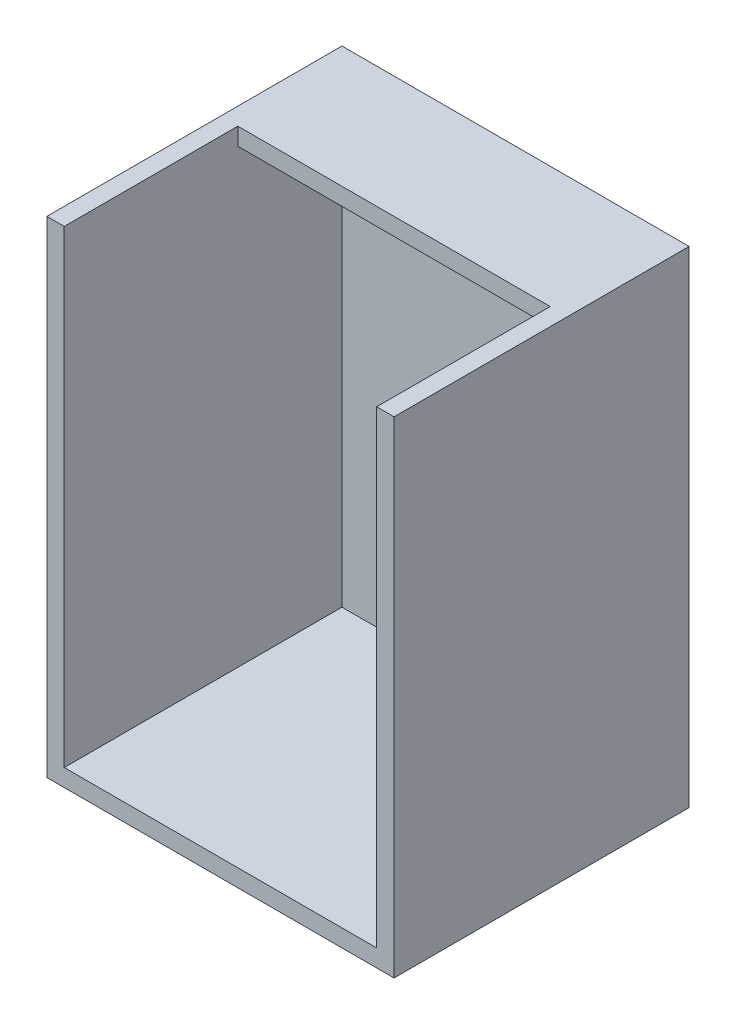
SolidWorks part; units mm, degrees
ref_plane "Front Plane" through (0, 0, 0) normal (1, 0, 0) x (0, 1, 0)
ref_plane "Top Plane" through (0, 0, 0) normal (0, 0, 1) x (0, 1, 0)
ref_plane "Right Plane" through (0, 0, 0) normal (0, 1, 0) x (-1, 0, 0)
sketch "Sketch2" plane through (0, 0, 0) normal (0, 0, 1) x (0, 1, 0)
  line L1 (-70, 50) -> (70, 50)
  line L2 (-70, 50) -> (-70, -50)
  line L3 (-70, -50) -> (70, -50)
  line L4 (70, 50) -> (70, -50)
  line L5 (-70, 50) -> (70, -50) construction
  line L6 (-70, -50) -> (70, 50) construction
  point P0 (0, 0)
  dimension "D1" = 100
  dimension "D2" = 140
extrude "Boss-Extrude1" add sketch "Sketch2" along normal blind 5
sketch "Sketch3" plane through (0, 0, 5) normal (0, 0, 1) x (1, 0, 0)
  line L0 (-45, 65) -> (45, 65)
  line L1 (-50, 70) -> (50, 70)
  line L2 (-50, 70) -> (-50, -70)
  line L3 (-50, -70) -> (50, -70)
  line L4 (50, 70) -> (50, -70)
  line L5 (-50, 70) -> (50, -70) construction
  line L6 (-50, -70) -> (50, 70) construction
  line L7 (45, 65) -> (45, -65)
  line L8 (-45, -65) -> (45, -65)
  line L9 (-45, 65) -> (-45, -65)
  point P0 (0, 0)
  dimension "D1" = 5
extrude "Boss-Extrude2" add sketch "Sketch3" along normal blind 30
sketch "Sketch4" plane through (0, 0, 0) normal (0, 0, 1) x (0, 1, 0)
  line L0 (70, 50) -> (-70, 50)
  line L1 (-70, 50) -> (-70, -50)
  line L2 (-70, -50) -> (70, -50)
  line L3 (70, -50) -> (70, -45)
  line L4 (70, -50) -> (70, 50) construction
  line L5 (70, -45) -> (-65, -45)
  line L6 (-65, -45) -> (-65, 45)
  line L7 (-65, 45) -> (70, 45)
  line L8 (70, 45) -> (70, 50)
extrude "Boss-Extrude3" add sketch "Sketch4" along normal blind 50 from surface at 35 starting at face at (0, 0, 35)
